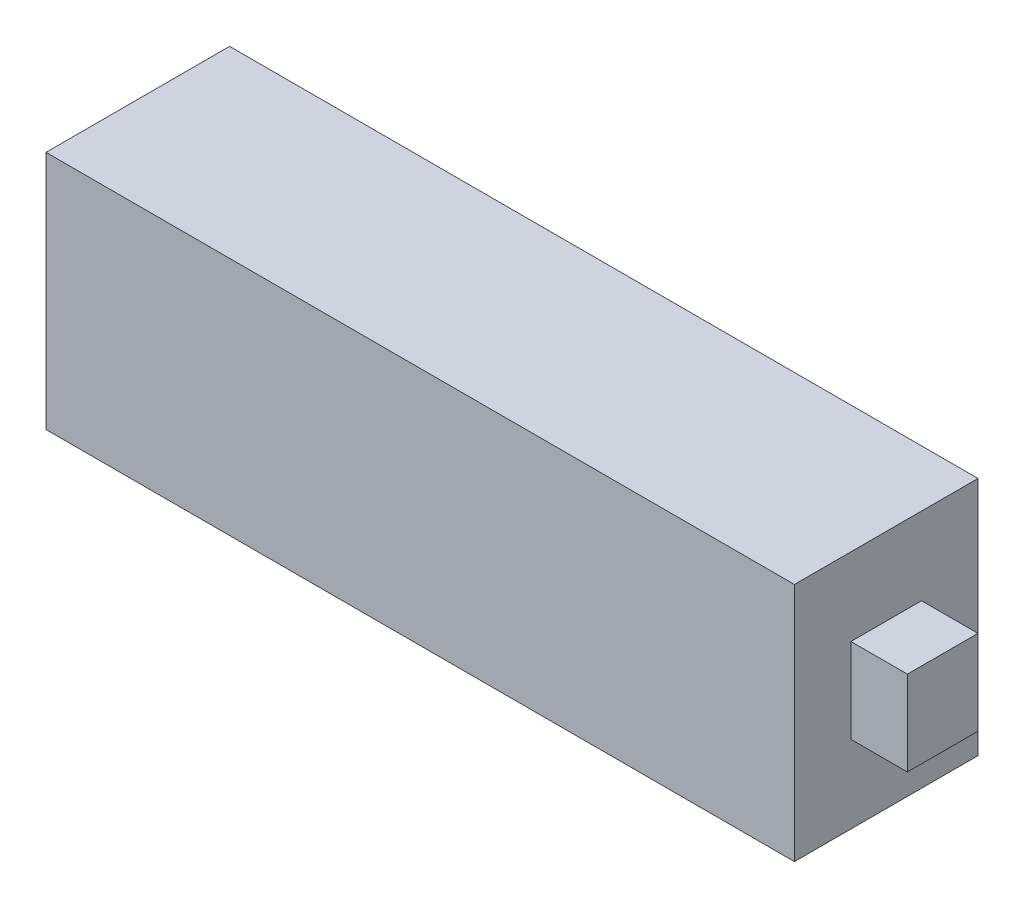
SolidWorks part; units mm, degrees
ref_plane "Front Plane" through (0, 0, 0) normal (0, 0, 1) x (1, 0, 0)
ref_plane "Top Plane" through (0, 0, 0) normal (0, 1, 0) x (1, 0, 0)
ref_plane "Right Plane" through (0, 0, 0) normal (1, 0, 0) x (0, 0, -1)
sketch "Sketch1" plane through (0, 0, 0) normal (0, 0, 1) x (1, 0, 0)
  line L0 (-53, -17) -> (53, -17)
  line L1 (53, -17) -> (53, 17)
  line L2 (53, 17) -> (-53, 17)
  line L3 (-53, 17) -> (-53, -17)
extrude "Pack" add sketch "Sketch1" along normal blind 26
ref_plane "P_Front_8" through (0, 0, 8) normal (0, 0, 1) x (1, 0, 0)
sketch "Sketch2" plane through (0, 0, 8) normal (0, 0, 1) x (1, 0, 0)
  line L0 (53, -6) -> (61, -6)
  line L1 (61, -6) -> (61, 6)
  line L2 (61, 6) -> (53, 6)
  line L3 (53, 6) -> (53, -6)
extrude "Lead_exit" add sketch "Sketch2" along normal blind 10
